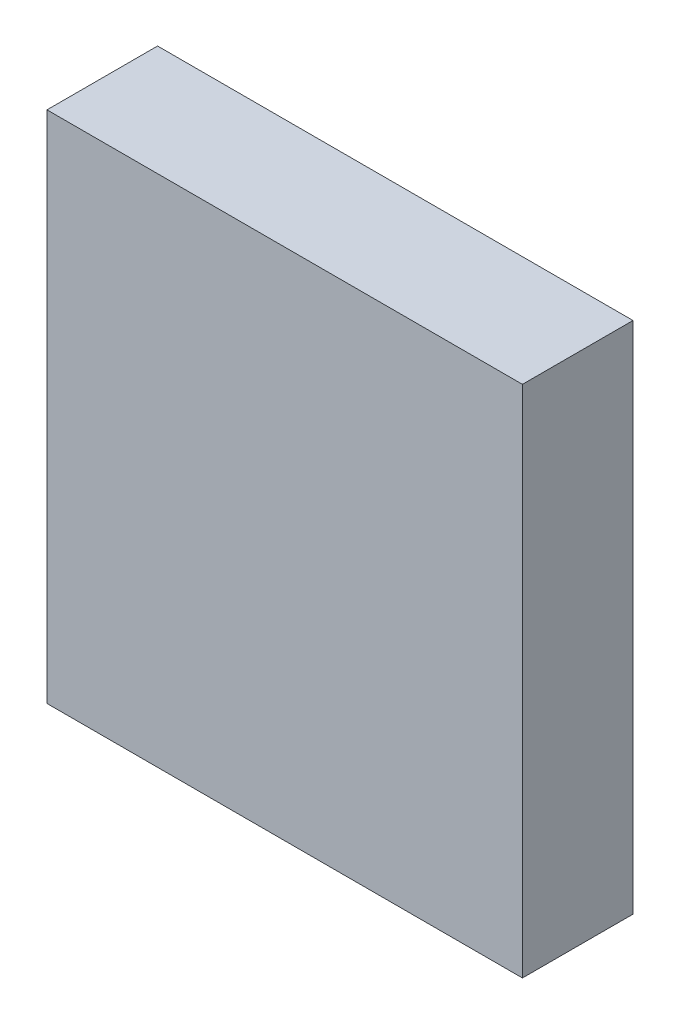
SolidWorks part; units mm, degrees
ref_plane "Front Plane" through (0, 0, 0) normal (0, 0, 1) x (1, 0, 0)
ref_plane "Top Plane" through (0, 0, 0) normal (0, 1, 0) x (1, 0, 0)
ref_plane "Right Plane" through (0, 0, 0) normal (1, 0, 0) x (0, 0, -1)
sketch "Sketch1" plane through (0, 0, 0) normal (0, 0, 1) x (1, 0, 0)
  line L1 (-215, 232.5) -> (215, 232.5)
  line L2 (-215, 232.5) -> (-215, -232.5)
  line L3 (-215, -232.5) -> (215, -232.5)
  line L4 (215, 232.5) -> (215, -232.5)
  line L5 (-215, 232.5) -> (215, -232.5) construction
  line L6 (-215, -232.5) -> (215, 232.5) construction
  point P0 (0, 0)
  dimension "D1" = 465
  dimension "D2" = 430
extrude "Boss-Extrude1" add sketch "Sketch1" along normal mid plane 100
